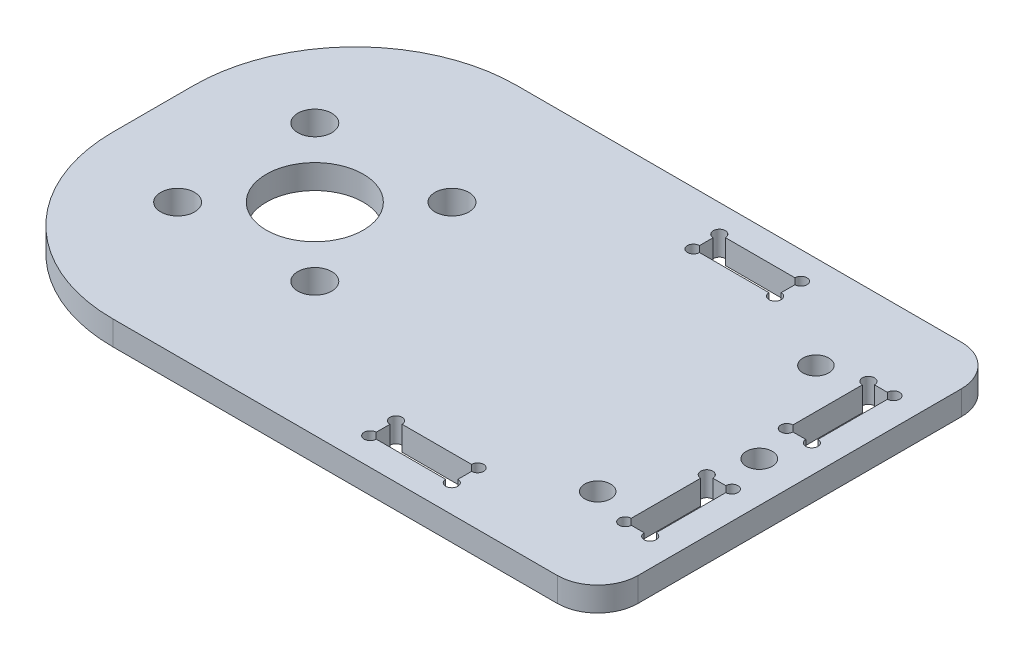
SolidWorks part; units mm, degrees
ref_plane "前视基准面" through (0, 0, 0) normal (0, 0, 1) x (1, 0, 0)
ref_plane "上视基准面" through (0, 0, 0) normal (0, 1, 0) x (1, 0, 0)
ref_plane "右视基准面" through (0, 0, 0) normal (1, 0, 0) x (0, 0, -1)
other "Configuration Table"
sketch "草图1" plane through (0, 0, 0) normal (0, 1, 0) x (1, 0, 0)
  line L1 (0, 0) -> (80, 0)
  line L2 (0, 0) -> (0, -50)
  line L3 (0, -50) -> (80, -50)
  line L4 (80, 0) -> (80, -50)
  dimension "D1" = 50
  dimension "D2" = 80
extrude "凸台-拉伸1" add sketch "草图1" along normal blind 3
sketch "草图2" plane through (0, 3, 0) normal (0, 1, 0) x (1, 0, 0)
  line L0 (0, -25) -> (40, -25) construction
  line L1 (0, 0) -> (0, -50) construction
  line L2 (11.5147, -16.5147) -> (28.4853, -33.4853) construction
  line L3 (28.4853, -16.5147) -> (11.5147, -33.4853) construction
  circle A0 centre (20, -25) radius 6
  circle A1 centre (20, -25) radius 12 construction
  circle A2 centre (11.5147, -16.5147) radius 2.1
  circle A3 centre (28.4853, -16.5147) radius 2.1
  circle A4 centre (28.4853, -33.4853) radius 2.1
  circle A5 centre (11.5147, -33.4853) radius 2.1
  dimension "D1" = 12
  dimension "D2" = 24
  dimension "D7" = 4.2
  dimension "D3" = 45
  dimension "D4" = 45
  dimension "D5" = 24
  dimension "D6" = 20
extrude "切除-拉伸1" cut sketch "草图2" against normal blind 3
sketch "草图3" plane through (0, 3, 0) normal (0, 1, 0) x (1, 0, 0)
  line L0 (80, -25) -> (31.3903, -25) construction
  line L1 (80, -50) -> (80, 0) construction
  line L2 (73.45, -15) -> (76.55, -15) construction
  line L3 (73.45, -9.95) -> (76.55, -9.95)
  line L4 (73.45, -9.95) -> (73.45, -20.05)
  line L5 (73.45, -20.05) -> (76.55, -20.05)
  line L6 (76.55, -9.95) -> (76.55, -20.05)
  line L7 (75, -9.95) -> (75, -20.05) construction
  line L8 (73.45, -29.95) -> (76.55, -29.95)
  line L9 (76.55, -40.05) -> (76.55, -29.95)
  line L10 (73.45, -40.05) -> (76.55, -40.05)
  line L11 (73.45, -40.05) -> (73.45, -29.95)
  line L12 (75, -25) -> (75, -20.05) construction
  circle A0 centre (75, -25) radius 1.61
  dimension "D5" = 3.22
  dimension "D1" = 10.1
  dimension "D2" = 3.1
  dimension "D3" = 10
  dimension "D4" = 5
extrude "切除-拉伸2" cut sketch "草图3" against normal blind 3
sketch "草图4" plane through (0, 3, 0) normal (0, 1, 0) x (1, 0, 0)
  line L0 (48.45, -5) -> (58.55, -5) construction
  line L1 (48.45, -3.4) -> (58.55, -3.4)
  line L2 (48.45, -3.4) -> (48.45, -6.6)
  line L3 (48.45, -6.6) -> (58.55, -6.6)
  line L4 (58.55, -3.4) -> (58.55, -6.6)
  line L5 (53.5, -3.4) -> (53.5, -6.6) construction
  line L6 (80, 0) -> (0, 0) construction
  line L7 (75, -9.95) -> (75, -4.308) construction
  line L8 (76.55, -9.95) -> (73.45, -9.95) construction
  line L9 (80, -25) -> (46.9343, -25) construction
  line L10 (80, -50) -> (80, 0) construction
  line L11 (48.45, -43.4) -> (58.55, -43.4)
  line L12 (58.55, -46.6) -> (58.55, -43.4)
  line L13 (48.45, -46.6) -> (58.55, -46.6)
  line L14 (48.45, -46.6) -> (48.45, -43.4)
  circle A0 centre (68.5, -11.5) radius 1.6
  circle A1 centre (68.5, -38.5) radius 1.6
  dimension "D5" = 3.2
  dimension "D1" = 3.2
  dimension "D2" = 10.1
  dimension "D3" = 5
  dimension "D4" = 21.5
  dimension "D6" = 6.5
  dimension "7.5" = 6.5
extrude "切除-拉伸3" cut sketch "草图4" against normal through all
fillet "圆角1" radius 20 2 edges at (0, 1.5, 50) (0, 1.5, 0)
fillet "圆角2" radius 5 2 edges at (80, 1.5, 50) (80, 1.5, 0)
sketch "草图5" plane through (0, 3, 0) normal (0, 1, 0) x (1, 0, 0)
  line L0 (80, -25) -> (45.4363, -25) construction
  line L1 (80, -45) -> (80, -5) construction
  circle A0 centre (48.45, -3.4) radius 0.75
  circle A1 centre (48.45, -6.6) radius 0.75
  circle A2 centre (58.55, -6.6) radius 0.75
  circle A3 centre (58.55, -3.4) radius 0.75
  circle A4 centre (73.45, -9.95) radius 0.75
  circle A5 centre (76.55, -9.95) radius 0.75
  circle A6 centre (76.55, -20.05) radius 0.75
  circle A7 centre (73.45, -20.05) radius 0.75
  circle A8 centre (73.45, -29.95) radius 0.75
  circle A9 centre (76.55, -29.95) radius 0.75
  circle A10 centre (76.55, -40.05) radius 0.75
  circle A11 centre (73.45, -40.05) radius 0.75
  circle A12 centre (58.55, -46.6) radius 0.75
  circle A13 centre (58.55, -43.4) radius 0.75
  circle A14 centre (48.45, -43.4) radius 0.75
  circle A15 centre (48.45, -46.6) radius 0.75
  dimension "D1" = 1.5
extrude "切除-拉伸4" cut sketch "草图5" against normal through all
